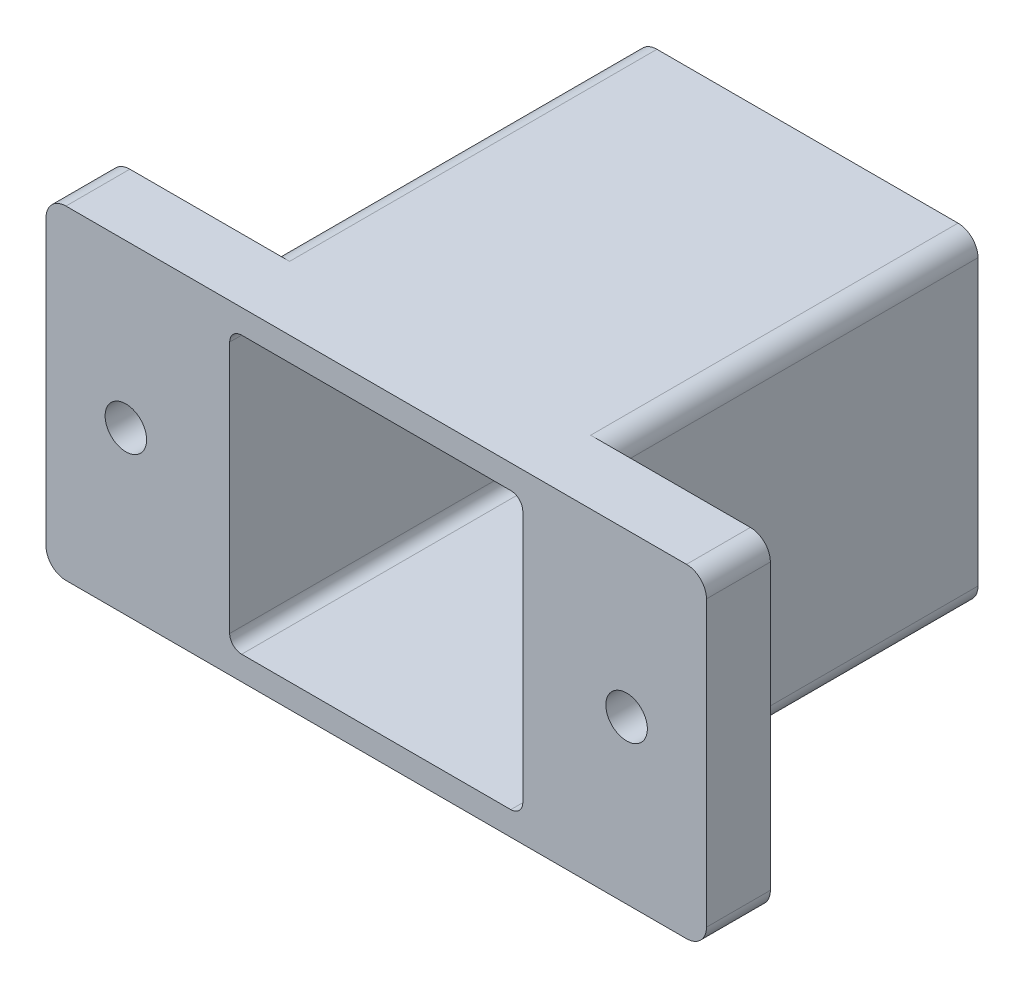
SolidWorks part; units mm, degrees
ref_plane "Спереди" through (0, 0, 0) normal (0, 0, 1) x (1, 0, 0)
ref_plane "Сверху" through (0, 0, 0) normal (0, 1, 0) x (1, 0, 0)
ref_plane "Справа" through (0, 0, 0) normal (1, 0, 0) x (0, 0, -1)
sketch "Эскиз1" plane through (0, 0, 0) normal (0, 0, 1) x (1, 0, 0)
  line L0 (-18.35, 17.3) -> (18.35, -17.3) construction
  line L1 (-18.35, 17.3) -> (18.35, 17.3)
  line L2 (-18.35, 17.3) -> (-18.35, -17.3)
  line L3 (-18.35, -17.3) -> (18.35, -17.3)
  line L4 (18.35, 17.3) -> (18.35, -17.3)
  line L13 (-21.35, 20.3) -> (-21.35, -20.3)
  line L14 (-21.35, -20.3) -> (21.35, -20.3)
  line L15 (21.35, 20.3) -> (21.35, -20.3)
  line L16 (-21.35, 20.3) -> (21.35, 20.3)
  point P4 (0, 0)
  dimension "D1" = 34.6
  dimension "D2" = 36.7
  dimension "D3" = 3
extrude "Бобышка-Вытянуть1" add sketch "Эскиз1" along normal blind 50
sketch "Эскиз2" plane through (0, 0, 0) normal (0, 0, -1) x (-1, 0, 0)
  line L0 (-21.35, 20.3) -> (21.35, -20.3) construction
  line L4 (21.35, 20.3) -> (-21.35, 20.3)
  line L5 (-21.35, 20.3) -> (-21.35, -20.3)
  line L6 (-21.35, -20.3) -> (21.35, -20.3)
  line L7 (21.35, -20.3) -> (21.35, 20.3)
  line L8 (21.35, 20.3) -> (-21.35, 20.3)
  line L9 (-21.35, 20.3) -> (-21.35, -20.3)
  line L10 (-21.35, -20.3) -> (21.35, -20.3)
  line L11 (21.35, -20.3) -> (21.35, 20.3)
  circle A0 centre (0, 0) radius 7.5
  dimension "D2" = 15
  dimension "D1" = 0
extrude "Бобышка-Вытянуть2" add sketch "Эскиз2" along normal blind 4
sketch "Эскиз3" plane through (0, 0, 50) normal (0, 0, 1) x (1, 0, 0)
  line L1 (-21.35, 20.3) -> (-41.35, 20.3)
  line L2 (-21.35, 20.3) -> (-21.35, -20.3)
  line L3 (-21.35, -20.3) -> (-41.35, -20.3)
  line L4 (-41.35, 20.3) -> (-41.35, -20.3)
  dimension "D2" = 20
extrude "Бобышка-Вытянуть3" add sketch "Эскиз3" against normal blind 8
sketch "Эскиз4" plane through (0, 0, 50) normal (0, 0, 1) x (1, 0, 0)
  line L0 (-41.35, 20.3) -> (-41.35, -20.3) construction
  line L1 (-41.35, 0) -> (49958.65, 0) construction
  circle A0 centre (-31.35, 0) radius 2.6
  point P4 (-41.35, 0)
  dimension "D1" = 5.2
  dimension "D2" = 10
extrude "Вырез-Вытянуть1" cut sketch "Эскиз4" against normal through all
sketch "Эскиз5" plane through (0, 0, 42) normal (0, 0, -1) x (-1, 0, 0)
  line L1 (36.0843, 0) -> (33.7171, 4.1)
  line L2 (33.7171, 4.1) -> (28.9829, 4.1)
  line L3 (28.9829, 4.1) -> (26.6157, 0)
  line L4 (26.6157, 0) -> (28.9829, -4.1)
  line L5 (28.9829, -4.1) -> (33.7171, -4.1)
  line L6 (33.7171, -4.1) -> (36.0843, 0)
  circle A0 centre (31.35, 0) radius 4.1 construction
  dimension "D1" = 8.2
extrude "Вырез-Вытянуть2" cut sketch "Эскиз5" against normal blind 4
mirror "Зеркальное отражение1" about plane through (0, 0, 0) normal (1, 0, 0) of "Бобышка-Вытянуть3", "Вырез-Вытянуть1", "Вырез-Вытянуть2"
fillet "Скругление1" radius 2.5 8 edges at (41.35, -20.3, 46) (41.35, 20.3, 46) (-41.35, -20.3, 46) (-41.35, 20.3, 46) (21.35, 20.3, 19) (21.35, -20.3, 19) (-21.35, -20.3, 19) (-21.35, 20.3, 19)
fillet "Скругление2" radius 1.5 4 edges at (18.35, 17.3, 25) (-18.35, 17.3, 25) (-18.35, -17.3, 25) (18.35, -17.3, 25)
